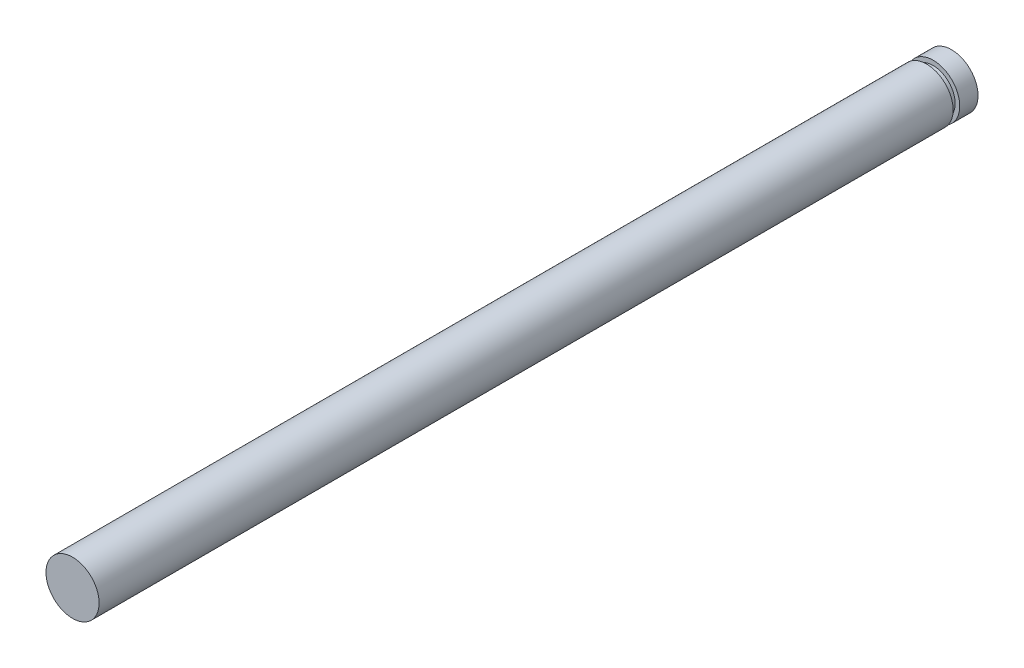
SolidWorks part; units mm, degrees
material "Chrome Stainless Steel"
ref_plane "Front Plane" through (0, 0, 0) normal (0, 0, 1) x (1, 0, 0)
ref_plane "Top Plane" through (0, 0, 0) normal (0, 1, 0) x (1, 0, 0)
ref_plane "Right Plane" through (0, 0, 0) normal (1, 0, 0) x (0, 0, -1)
sketch "Sketch1" plane through (0, 0, 0) normal (1, 0, 0) x (0, 0, -1)
  line L0 (126.2743, 0) -> (-126.2743, 0) construction
  line L1 (304.8, 0) -> (304.8, 18.415)
  line L2 (304.8, 18.415) -> (292.1, 18.415)
  line L3 (292.1, 18.415) -> (292.1, 15.24)
  line L4 (292.1, 15.24) -> (287.528, 15.24)
  line L5 (287.528, 15.24) -> (287.528, 18.415)
  line L6 (287.528, 18.415) -> (-304.8, 18.415)
  line L7 (-304.8, 18.415) -> (-304.8, 0)
  line L8 (304.8, 0) -> (-304.8, 0)
  point P4 (0, 0)
  point P7 (304.8, 9.2075)
  dimension "D1" = 18.415
  dimension "D2" = 18.415
  dimension "D3" = 30.48
  dimension "D4" = 609.6
  dimension "D5" = 304.8
  dimension "D6" = 12.7
  dimension "D7" = 4.572
revolve "Revolve1" add sketch "Sketch1" angle 360 about L0
